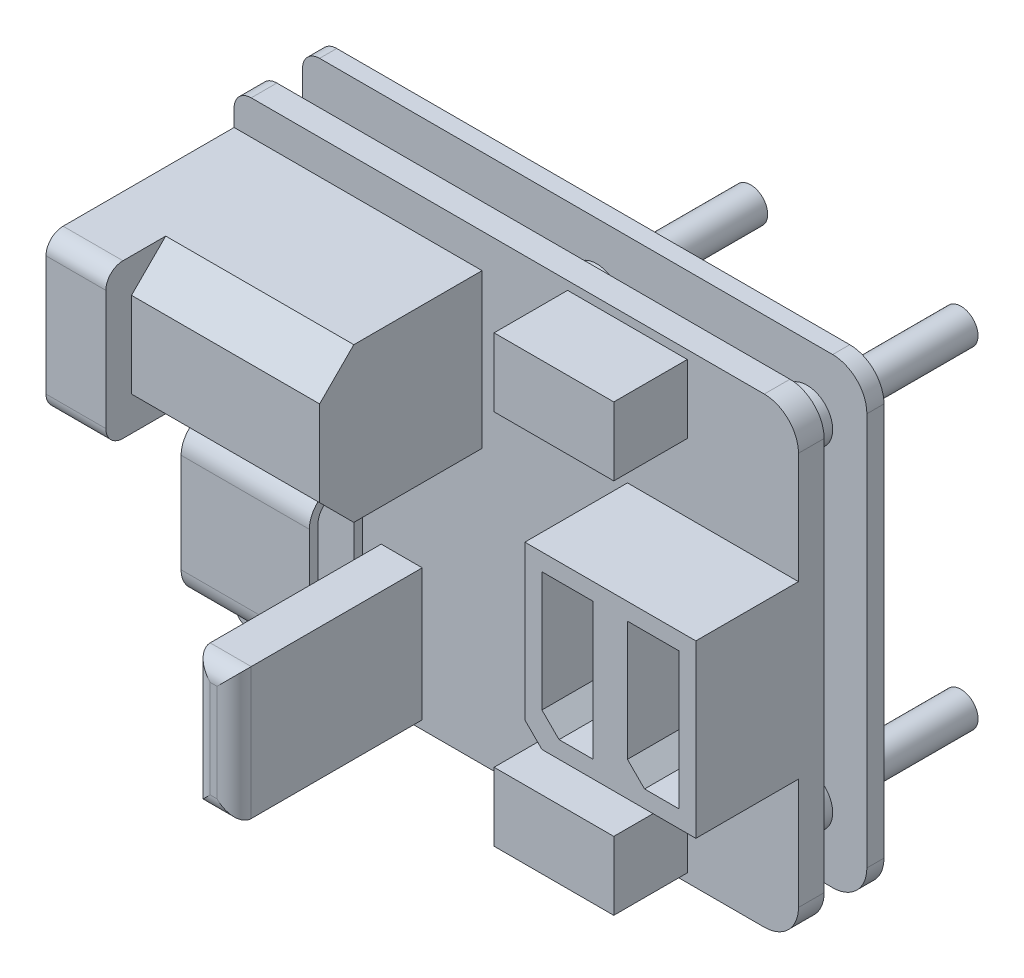
SolidWorks part; units mm, degrees
material "PEI"
ref_plane "前视基准面" through (0, 0, 0) normal (0, 0, 1) x (1, 0, 0)
ref_plane "上视基准面" through (0, 0, 0) normal (0, 1, 0) x (1, 0, 0)
ref_plane "右视基准面" through (0, 0, 0) normal (1, 0, 0) x (0, 0, -1)
other "Configuration Table"
sketch "草图1" plane through (0, 0, 0) normal (0, 0, 1) x (1, 0, 0)
  line L1 (0, 0) -> (33, 0)
  line L2 (0, 0) -> (0, 27)
  line L3 (0, 27) -> (33, 27)
  line L4 (33, 0) -> (33, 27)
  dimension "D1" = 33
  dimension "D2" = 27
extrude "凸台-拉伸1" add sketch "草图1" along normal blind 5
fillet "圆角1" radius 2 2 edges at (33, 27, 2.5) (33, 0, 2.5)
sketch "草图2" plane through (0, 0, 0) normal (0, 0, -1) x (-1, 0, 0)
  line L0 (-33, 13.5) -> (0, 13.5) construction
  line L1 (-33, 2) -> (-33, 25) construction
  line L2 (0, 27) -> (0, 0) construction
  circle A0 centre (-17.2, 23.2) radius 1
  circle A1 centre (-29.5, 23.2) radius 1
  circle A2 centre (-29.5, 3.8) radius 1
  circle A3 centre (-17.2, 3.8) radius 1
  point P8 (0, 0)
  point P9 (0, 0)
  point P16 (0, 0)
  dimension "D1" = 2
  dimension "D2" = 19.4
  dimension "D3" = 12.3
  dimension "D4" = 3.5
extrude "凸台-拉伸2" add sketch "草图2" along normal blind 8
sketch "草图3" plane through (0, 0, 5) normal (0, 0, 1) x (1, 0, 0)
  line L0 (0, 13.5) -> (33, 13.5) construction
  line L1 (0, 27) -> (0, 0) construction
  line L2 (33, 2) -> (33, 25) construction
  line L4 (33, 18.5) -> (23, 18.5)
  line L5 (33, 18.5) -> (33, 8.5)
  line L6 (33, 8.5) -> (23, 8.5)
  line L7 (23, 18.5) -> (23, 8.5)
  point P10 (23, 13.5)
  dimension "D1" = 10
  dimension "D2" = 10
extrude "凸台-拉伸3" add sketch "草图3" along normal blind 6
chamfer "倒角1" distance 1 angle 45 1 edges at (23, 8.5, 8)
sketch "草图4" plane through (0, 0, 11) normal (0, 0, 1) x (1, 0, 0)
  line L0 (33, 18.5) -> (23, 18.5) construction
  line L1 (24, 17.5) -> (27, 17.5)
  line L2 (24, 17.5) -> (24, 10.5)
  line L3 (25, 9.5) -> (27, 9.5)
  line L4 (27, 17.5) -> (27, 9.5)
  line L5 (29, 17.5) -> (32, 17.5)
  line L6 (29, 17.5) -> (29, 10.5)
  line L7 (30, 9.5) -> (32, 9.5)
  line L8 (32, 17.5) -> (32, 9.5)
  line L9 (24, 8.5) -> (33, 8.5) construction
  line L10 (23, 18.5) -> (23, 9.5) construction
  line L11 (33, 8.5) -> (33, 18.5) construction
  line L12 (24, 10.5) -> (25, 9.5)
  line L13 (29, 10.5) -> (30, 9.5)
  point P2 (24, 9.5)
  point P6 (29, 9.5)
  dimension "D1" = 1
  dimension "D2" = 1
  dimension "D3" = 2
  dimension "D4" = 1
  dimension "D5" = 1
extrude "切除-拉伸1" cut sketch "草图4" against normal blind 4
sketch "草图5" plane through (0, 0, 5) normal (0, 0, 1) x (1, 0, 0)
  line L0 (0, 27) -> (0, 0) construction
  line L1 (0, 25) -> (14.5, 25)
  line L2 (0, 25) -> (0, 16)
  line L3 (0, 16) -> (14.5, 16)
  line L4 (14.5, 25) -> (14.5, 16)
  line L5 (31, 27) -> (0, 27) construction
  line L6 (0, 0) -> (31, 0) construction
  line L7 (8.6, 8.2) -> (11, 8.2)
  line L8 (8.6, 8.2) -> (8.6, 0.5)
  line L9 (8.6, 0.5) -> (11, 0.5)
  line L10 (11, 8.2) -> (11, 0.5)
  dimension "D1" = 2
  dimension "D2" = 9
  dimension "D3" = 14.5
  dimension "D4" = 7.7
  dimension "D5" = 2.4
  dimension "D6" = 0.5
  dimension "D7" = 11
extrude "凸台-拉伸4" add sketch "草图5" along normal blind 11
sketch "草图6" plane through (0, 0, 0) normal (-1, 0, 0) x (0, 0, 1)
  line L0 (16, 25) -> (16, 16) construction
  circle A0 centre (11.55, 20.5) radius 2.85
  circle A1 centre (11.55, 20.5) radius 0.5
  point P4 (16, 20.5)
  dimension "D1" = 5.7
  dimension "D3" = 1
  dimension "D2" = 4.45
extrude "切除-拉伸2" cut sketch "草图6" against normal blind 8 draft 3
sketch "草图7" plane through (14.5, 0, 0) normal (1, 0, 0) x (0, 0, -1)
  line L0 (-14.5, 23) -> (-14.5, 18)
  line L1 (-14.5, 18) -> (-12.5, 16)
  line L2 (-12.5, 25) -> (-14.5, 23)
  line L4 (-5, 16) -> (-5, 25)
  line L5 (-5, 25) -> (-16, 25)
  line L6 (-16, 25) -> (-16, 16)
  line L7 (-16, 16) -> (-5, 16)
  line L8 (-5, 16) -> (-5, 25)
  line L9 (-5, 25) -> (-12.5, 25)
  line L11 (-12.5, 16) -> (-5, 16)
  point P2 (-14.5, 25)
  point P4 (-14.5, 16)
  line M9 (-5, 25) -> (-16, 25)
  line M10 (-16, 25) -> (-16, 16)
  line M11 (-16, 16) -> (-5, 16)
  dimension "D2" = 9.5
  dimension "D1" = 0
extrude "切除-拉伸3" cut sketch "草图7" against normal offset from surface (11 mm away) 3.5 contours L2 L1 L0 M9 M10 M11 up to face at (0, 20.5, 12.05)
sketch "草图8" plane through (0, 0, 0) normal (-1, 0, 0) x (0, 0, 1)
  line L0 (6.55, 9.95) -> (6.55, 4.15) construction
  line L1 (8.1, 9.95) -> (8.1, 4.15)
  line L2 (5, 9.95) -> (5, 4.15)
  line L3 (5, 16) -> (5, 0) construction
  line L4 (5, 0) -> (0, 0) construction
  line L5 (7.6, 9.95) -> (7.6, 4.15)
  line L6 (5.5, 9.95) -> (5.5, 4.15)
  arc A0 (8.1, 9.95) -> (5, 9.95) centre (6.55, 9.95) ccw
  arc A1 (5, 4.15) -> (8.1, 4.15) centre (6.55, 4.15) ccw
  arc A2 (5.5, 4.15) -> (7.6, 4.15) centre (6.55, 4.15) ccw
  arc A3 (7.6, 9.95) -> (5.5, 9.95) centre (6.55, 9.95) ccw
  point P2 (6.55, 7.05)
  point P9 (6.55, 11.5)
  point P10 (6.55, 2.6)
  dimension "D1" = 3.1
  dimension "D2" = 8.9
  dimension "D3" = 11.5
  dimension "D4" = 0.5
extrude "凸台-拉伸5" add sketch "草图8" against normal blind 7.5
sketch "草图9" plane through (0, 0, 5) normal (0, 0, 1) x (1, 0, 0)
  line L0 (33, 13.5) -> (0, 13.5) construction
  line L1 (33, 8.5) -> (33, 18.5) construction
  line L2 (0, 16) -> (0, 9.95) construction
  line L3 (31, 27) -> (0, 27) construction
  line L4 (19.5, 26.5) -> (26.5, 26.5)
  line L5 (19.5, 26.5) -> (19.5, 22.5)
  line L6 (19.5, 22.5) -> (26.5, 22.5)
  line L7 (26.5, 26.5) -> (26.5, 22.5)
  line L8 (33, 18.5) -> (33, 25) construction
  line L9 (26.5, 0.5) -> (26.5, 4.5)
  line L10 (19.5, 0.5) -> (26.5, 0.5)
  line L11 (19.5, 0.5) -> (19.5, 4.5)
  line L12 (19.5, 4.5) -> (26.5, 4.5)
  dimension "D1" = 4
  dimension "D2" = 7
  dimension "D3" = 0.5
  dimension "D4" = 13.5
extrude "凸台-拉伸6" add sketch "草图9" along normal blind 4.3
fillet "圆角2" radius 1 8 edges at (1.75, 16, 16) (8.6, 4.35, 16) (9.8, 0.5, 16) (11, 4.35, 16) (9.8, 8.2, 16) (1.75, 25, 16) (0, 27, 2.5) (0, 0, 2.5)
sketch "草图10" plane through (0, 0, 0) normal (0, 0, -1) x (-1, 0, 0)
  line L4 (-31, 0) -> (-1, 0)
  line L5 (0, 1) -> (0, 26)
  line L6 (-1, 27) -> (-31, 27)
  line L7 (-33, 25) -> (-33, 2)
  line L8 (-31, 0) -> (-1, 0)
  line L9 (0, 1) -> (0, 26)
  line L10 (-1, 27) -> (-31, 27)
  line L11 (-33, 25) -> (-33, 2)
  circle A0 centre (-17.2, 3.8) radius 1 construction
  circle A1 centre (-29.5, 3.8) radius 1 construction
  circle A2 centre (-17.2, 23.2) radius 1 construction
  circle A3 centre (-29.5, 23.2) radius 1 construction
  arc A4 (-1, 0) -> (0, 1) centre (-1, 1) ccw
  arc A5 (0, 26) -> (-1, 27) centre (-1, 26) ccw
  arc A6 (-31, 27) -> (-33, 25) centre (-31, 25) ccw
  arc A7 (-33, 2) -> (-31, 0) centre (-31, 2) ccw
  arc A8 (-1, 0) -> (0, 1) centre (-1, 1) ccw
  arc A9 (0, 26) -> (-1, 27) centre (-1, 26) ccw
  arc A10 (-31, 27) -> (-33, 25) centre (-31, 25) ccw
  arc A11 (-33, 2) -> (-31, 0) centre (-31, 2) ccw
  circle A12 centre (-17.2, 3.8) radius 1
  circle A13 centre (-29.5, 3.8) radius 1
  circle A14 centre (-17.2, 23.2) radius 1
  circle A15 centre (-29.5, 23.2) radius 1
  circle A16 centre (-29.5, 23.2) radius 1.5
  circle A17 centre (-17.2, 23.2) radius 1.5
  circle A18 centre (-29.5, 3.8) radius 1.5
  circle A19 centre (-17.2, 3.8) radius 1.5
  line M13 (-31, 0) -> (-1, 0)
  arc M14 (-1, 0) -> (0, 1) centre (-1, 1) ccw
  line M15 (0, 1) -> (0, 26)
  arc M16 (0, 26) -> (-1, 27) centre (-1, 26) ccw
  line M17 (-1, 27) -> (-31, 27)
  arc M18 (-31, 27) -> (-33, 25) centre (-31, 25) ccw
  line M19 (-33, 25) -> (-33, 2)
  arc M20 (-33, 2) -> (-31, 0) centre (-31, 2) ccw
  dimension "D1" = 0
  dimension "D2" = 0.5
extrude "切除-拉伸4" cut sketch "草图10" against normal offset from surface (2.5 mm away) 1.5 from offset 1 contours A19 A18 A17 A16 M20 M13 M14 M15 M16 M17 M18 M19 up to face at (23, 2.5, 5)
